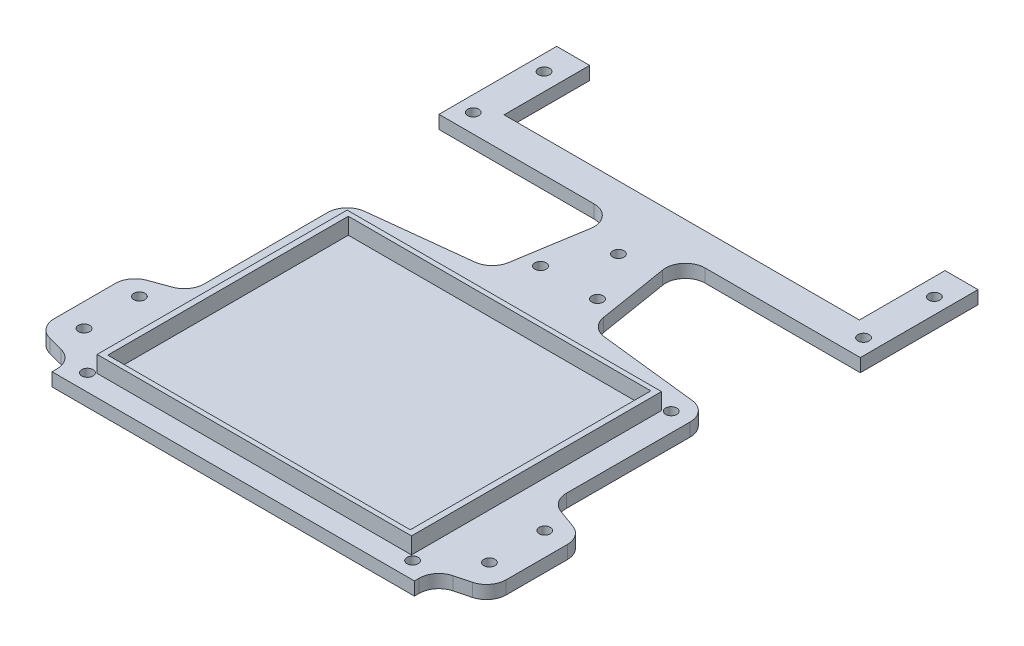
SolidWorks part; units mm, degrees
ref_plane "Front Plane" through (0, 0, 0) normal (0, 0, 1) x (1, 0, 0)
ref_plane "Top Plane" through (0, 0, 0) normal (0, 1, 0) x (1, 0, 0)
ref_plane "Right Plane" through (0, 0, 0) normal (1, 0, 0) x (0, 0, -1)
sketch "Sketch1" plane through (0, 0, 0) normal (0, 1, 0) x (1, 0, 0)
  line L0 (0, -119.0754) -> (0, 96.5159) construction
  line L1 (55, -97.2765) -> (-55, -97.2765)
  line L13 (-53.9437, 38.8785) -> (53.9437, 38.8785)
  line L27 (-63.9564, 29.1437) -> (-16.8537, 29.1437)
  line L28 (63.9564, 29.1437) -> (16.8537, 29.1437)
  line L36 (55.0051, -51.1098) -> (55.0503, -13.6249)
  line L37 (64.6762, -58.8392) -> (58.9521, -56.7549)
  line L38 (68.6233, -83.0239) -> (68.6233, -64.4771)
  line L39 (59.4999, -90.0271) -> (64.1233, -88.8333)
  line L40 (55, -97.2765) -> (55, -95.8366)
  line L41 (46.5, -89.196) -> (-46.5, -89.196)
  line L42 (-46.5, -89.196) -> (-46.5, -16.196)
  line L43 (-49.7222, -7.6554) -> (-19.6675, -4.2687)
  line L44 (49.7222, -7.6554) -> (19.6675, -4.2687)
  line L45 (-46.5, -16.196) -> (46.5, -16.196)
  line L46 (46.5, -89.196) -> (46.5, -16.196)
  line L47 (-10.9314, 22.1814) -> (-14.417, 0.7312)
  line L48 (10.9314, 22.1814) -> (14.417, 0.7312)
  line L53 (-55, -97.2765) -> (-55, -95.8366)
  line L54 (53.9437, 38.8785) -> (53.9437, 64.8729)
  line L55 (53.9437, 64.8729) -> (63.9564, 64.8729)
  line L56 (63.9564, 64.8729) -> (63.9564, 29.1437)
  line L57 (-63.9564, 64.8729) -> (-63.9564, 29.1437)
  line L58 (-53.9437, 64.8729) -> (-63.9564, 64.8729)
  line L59 (-53.9437, 38.8785) -> (-53.9437, 64.8729)
  line L60 (-59.4999, -90.0271) -> (-64.1233, -88.8333)
  line L61 (-68.6233, -83.0239) -> (-68.6233, -64.4771)
  line L62 (-64.6762, -58.8392) -> (-58.9521, -56.7549)
  line L63 (-55.0051, -51.1098) -> (-55.0503, -13.6249)
  circle A0 centre (-59.25, 56.3355) radius 1.7
  circle A1 centre (-59.25, 34.8355) radius 1.7
  circle A2 centre (59.25, 34.8355) radius 1.7
  circle A3 centre (59.25, 56.3355) radius 1.7
  circle A4 centre (0, 19.6587) radius 1.7
  circle A6 centre (61.535, -64.2395) radius 1.7
  circle A7 centre (-8.6603, 4.6587) radius 1.7
  circle A8 centre (8.6603, 4.6587) radius 1.7
  circle A9 centre (61.535, -81.0395) radius 1.7
  circle A10 centre (-61.535, -81.0395) radius 1.7
  circle A11 centre (-61.535, -64.2395) radius 1.7
  arc A12 (68.6233, -83.0239) -> (64.1233, -88.8333) centre (62.6233, -83.0239) cw
  arc A13 (64.6762, -58.8392) -> (68.6233, -64.4771) centre (62.6233, -64.4771) cw
  arc A14 (-68.6233, -64.4771) -> (-64.6762, -58.8392) centre (-62.6233, -64.4771) cw
  arc A15 (-64.1233, -88.8333) -> (-68.6233, -83.0239) centre (-62.6233, -83.0239) cw
  arc A16 (-55, -95.8366) -> (-59.4999, -90.0271) centre (-61, -95.8366) ccw
  arc A17 (59.4999, -90.0271) -> (55, -95.8366) centre (61, -95.8366) ccw
  arc A18 (55.0051, -51.1098) -> (58.9521, -56.7549) centre (61.0051, -51.117) ccw
  arc A19 (-58.9521, -56.7549) -> (-55.0051, -51.1098) centre (-61.0051, -51.117) ccw
  arc A20 (49.7222, -7.6554) -> (55.0503, -13.6249) centre (49.0503, -13.6176) cw
  arc A21 (-55.0503, -13.6249) -> (-49.7222, -7.6554) centre (-49.0503, -13.6176) cw
  arc A22 (14.417, 0.7312) -> (19.6675, -4.2687) centre (20.3393, 1.6936) ccw
  arc A23 (-19.6675, -4.2687) -> (-14.417, 0.7312) centre (-20.3393, 1.6936) ccw
  arc A24 (16.8537, 29.1437) -> (10.9314, 22.1814) centre (16.8537, 23.1437) ccw
  arc A25 (-16.8537, 29.1437) -> (-10.9314, 22.1814) centre (-16.8537, 23.1437) cw
  circle A27 centre (-49.3657, -13.6757) radius 1.7
  circle A28 centre (-49.3657, -92.1891) radius 1.7
  circle A29 centre (49.3657, -92.1891) radius 1.7
  circle A30 centre (49.3657, -13.6757) radius 1.7
  point P18 (0, 38.8785)
  point P29 (0, -97.2765)
  point P40 (0, 38.8785)
  point P42 (0, -16.196)
  point P45 (0, -89.196)
  point P49 (0, -91.1891)
  point P51 (0, -14.6757)
  point P68 (0, 0)
  point P69 (-48.3657, -14.6757)
  point P72 (68.6233, -87.6714)
  point P75 (68.6233, -60.2765)
  point P78 (-68.6233, -60.2765)
  point P81 (-68.6233, -87.6714)
  point P84 (-55, -91.1891)
  point P87 (55, -91.1891)
  point P90 (55, -55.3157)
  point P93 (-55, -55.3157)
  point P96 (55.0568, -8.2565)
  point P99 (-55.0568, -8.2565)
  point P102 (15.1467, -3.7593)
  point P105 (-15.1467, -3.7593)
  point P108 (9.8, 29.1437)
  point P111 (-9.8, 29.1437)
  point P112 (0, 0)
  point P113 (0, 0)
  point P114 (0, 0)
  point P115 (0, 0)
  point P116 (0, 0)
  point P117 (0, 0)
  point P118 (0, 0)
  point P119 (0, 0)
  point P120 (0, 0)
  point P121 (0, 0)
  point P122 (0, 0)
  point P123 (-117.9082, -73.8274)
  dimension "D9" = 93
  dimension "D11" = 8.5051
  dimension "D12" = 8.0805
  dimension "D2" = 6
  dimension "D3" = 6
  dimension "D4" = 78.5134
  dimension "D1" = 110
  dimension "D5" = 21.5
  dimension "D6" = 118.5
  dimension "D7" = 30.2934
  dimension "D8" = 98.7314
  dimension "D10" = 73
extrude "Boss-Extrude2" add sketch "Sketch1" along normal blind 4
sketch "Sketch4" plane through (0, 4, 0) normal (0, 1, 0) x (1, 0, 0)
  line L31 (-45.9197, -16.416) -> (45.9197, -16.416)
  line L32 (-45.9197, -16.416) -> (-45.9197, -89.4487)
  line L33 (-45.9197, -89.4487) -> (45.9197, -89.4487)
  line L34 (45.9197, -89.4487) -> (45.9197, -16.416)
  line L35 (-47.718, -14.9859) -> (-47.718, -90.8788)
  line L36 (-47.718, -90.8788) -> (47.718, -90.8788)
  line L37 (47.718, -14.9859) -> (47.718, -90.8788)
  line L38 (-47.718, -14.9859) -> (47.718, -14.9859)
  point P13 (0, 0)
  point P14 (0, -89.5518)
  point P15 (442.723, -16.5518)
  point P20 (0, 0)
  point P21 (46.8326, -14.9859)
  dimension "D1" = 91.8394
  dimension "D2" = 73.0327
extrude "Boss-Extrude5" add sketch "Sketch4" along normal blind 5 contours L38 L35 L36 L37 L34 L33 L32 L31
